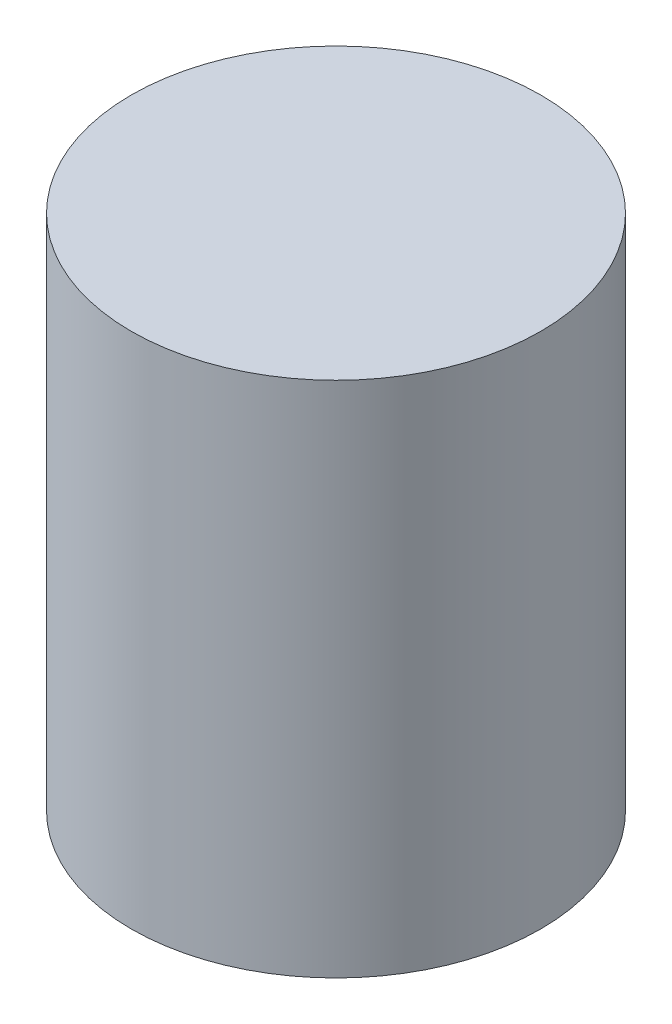
SolidWorks part; units mm, degrees
ref_plane "Front Plane" through (0, 0, 0) normal (0, 0, 1) x (1, 0, 0)
ref_plane "Top Plane" through (0, 0, 0) normal (0, 1, 0) x (1, 0, 0)
ref_plane "Right Plane" through (0, 0, 0) normal (1, 0, 0) x (0, 0, -1)
sketch "Sketch1" plane through (0, 0, 0) normal (0, 1, 0) x (1, 0, 0)
  circle A0 centre (0, 0) radius 23
extrude "Extrude-Thin1" add sketch "Sketch1" along normal blind 30 thin
sketch "Sketch2" plane through (0, 30, 0) normal (0, 1, 0) x (1, 0, 0)
  circle A1 centre (0, 0) radius 140
extrude "Boss-Extrude1" add sketch "Sketch2" along normal blind 2
sketch "Sketch3" plane through (0, 32, 0) normal (0, 1, 0) x (1, 0, 0)
  circle A0 centre (0, 0) radius 138
  circle A1 centre (0, 0) radius 140 construction
  circle A2 centre (0, 0) radius 140
  dimension "D1" = 2
extrude "Boss-Extrude2" add sketch "Sketch3" along normal blind 350
sketch "Sketch4" plane through (0, 382, 0) normal (0, 1, 0) x (1, 0, 0)
  circle A0 centre (0, 0) radius 140
extrude "Boss-Extrude3" add sketch "Sketch4" along normal blind 2
